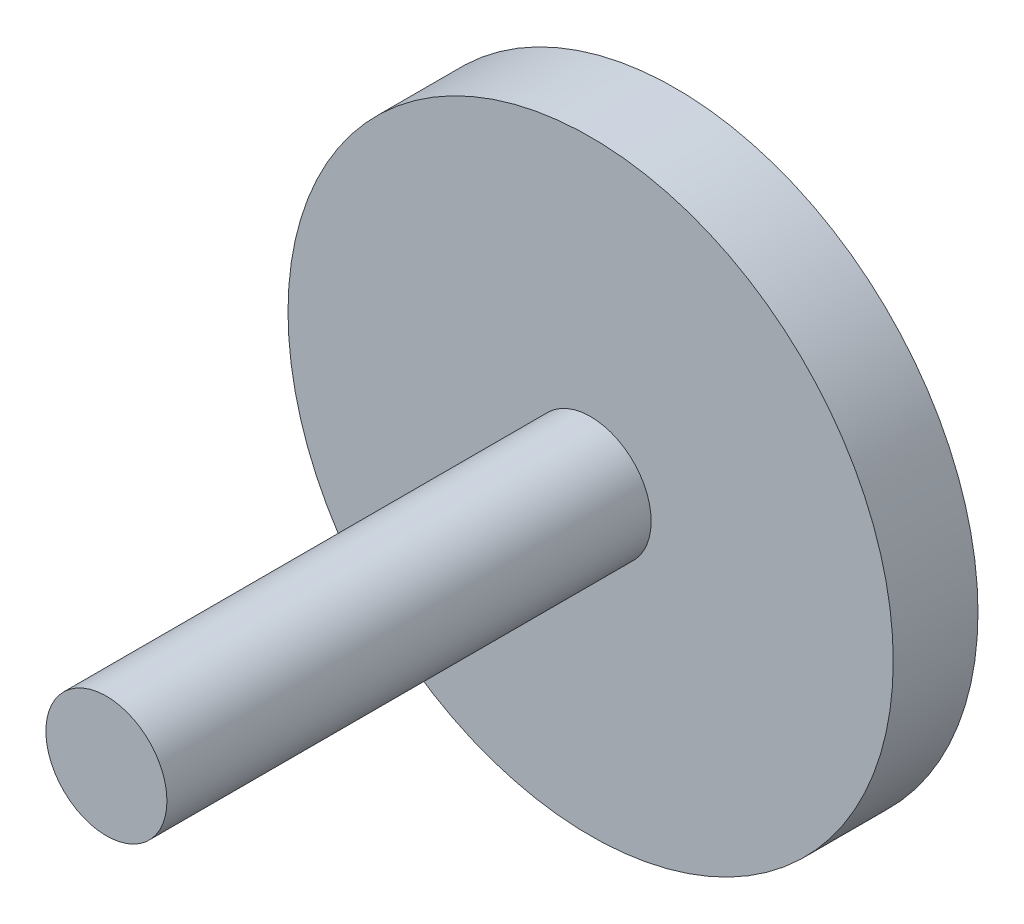
SolidWorks part; units mm, degrees
ref_plane "Front Plane" through (0, 0, 0) normal (0, 0, 1) x (1, 0, 0)
ref_plane "Top Plane" through (0, 0, 0) normal (0, 1, 0) x (1, 0, 0)
ref_plane "Right Plane" through (0, 0, 0) normal (1, 0, 0) x (0, 0, -1)
sketch "Sketch1" plane through (0, 0, 0) normal (0, 0, 1) x (1, 0, 0)
  circle A0 centre (0, 0) radius 25
  dimension "D1" = 50
extrude "Boss-Extrude1" add sketch "Sketch1" along normal blind 7
sketch "Sketch2" plane through (0, 0, 7) normal (0, 0, 1) x (1, 0, 0)
  circle A0 centre (0, 0) radius 5
  dimension "D1" = 10
extrude "Boss-Extrude2" add sketch "Sketch2" along normal blind 40
